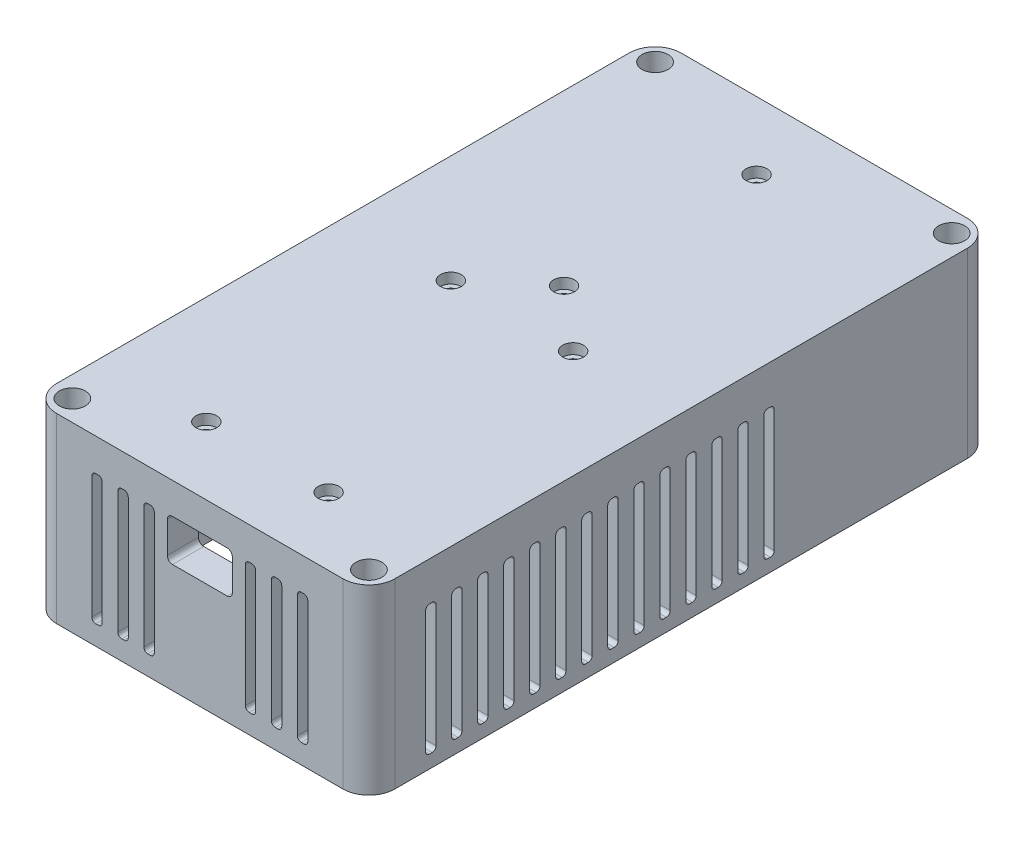
SolidWorks part; units mm, degrees
ref_plane "Front Plane" through (0, 0, 0) normal (0, 0, 1) x (1, 0, 0)
ref_plane "Top Plane" through (0, 0, 0) normal (0, 1, 0) x (1, 0, 0)
ref_plane "Right Plane" through (0, 0, 0) normal (1, 0, 0) x (0, 0, -1)
sketch "Sketch1" plane through (0, 0, 0) normal (0, 1, 0) x (1, 0, 0)
  line L0 (-26.5, 51.5) -> (-26.5, -51.5)
  line L1 (-27.5, 60) -> (27.5, 60)
  line L2 (-32.5, 55) -> (-32.5, -55)
  line L3 (-27.5, -60) -> (27.5, -60)
  line L4 (32.5, 55) -> (32.5, -55)
  line L5 (-32.5, 60) -> (32.5, -60) construction
  line L6 (-32.5, -60) -> (32.5, 60) construction
  line L7 (-24, -54) -> (24, -54)
  line L8 (26.5, 51.5) -> (26.5, -51.5)
  line L9 (-24, 54) -> (24, 54)
  line L10 (-26.5, -54) -> (26.5, -54) construction
  line L11 (-26.5, 54) -> (-26.5, -54) construction
  line L12 (26.5, 54) -> (26.5, -54) construction
  line L13 (-26.5, 54) -> (26.5, 54) construction
  arc A0 (-32.5, -55) -> (-27.5, -60) centre (-27.5, -55) ccw
  arc A1 (27.5, -60) -> (32.5, -55) centre (27.5, -55) ccw
  arc A2 (32.5, 55) -> (27.5, 60) centre (27.5, 55) ccw
  arc A3 (-27.5, 60) -> (-32.5, 55) centre (-27.5, 55) ccw
  arc A8 (-24, -54) -> (-26.5, -51.5) centre (-24, -51.5) cw
  arc A9 (-26.5, -54) -> (-26.5, -54) centre (-26.5, -54) ccw construction
  arc A10 (24, -54) -> (26.5, -51.5) centre (24, -51.5) ccw
  arc A11 (26.5, -54) -> (26.5, -54) centre (26.5, -54) ccw construction
  arc A12 (26.5, 51.5) -> (24, 54) centre (24, 51.5) ccw
  arc A13 (26.5, 54) -> (26.5, 54) centre (26.5, 54) ccw construction
  arc A14 (-24, 54) -> (-26.5, 51.5) centre (-24, 51.5) ccw
  arc A15 (-26.5, 54) -> (-26.5, 54) centre (-26.5, 54) ccw construction
  point P0 (0, 0)
  dimension "D3" = 5
  dimension "D5" = 2.5
  dimension "D1" = 120
  dimension "D2" = 65
  dimension "D4" = 6
extrude "Boss-Extrude1" add sketch "Sketch1" along normal blind 30
sketch "Sketch6" plane through (0, 30, 0) normal (0, 1, 0) x (1, 0, 0)
  line L1 (-27.5, 60) -> (27.5, 60)
  line L2 (-32.5, 55) -> (-32.5, -55)
  line L3 (-27.5, -60) -> (27.5, -60)
  line L4 (32.5, 55) -> (32.5, -55)
  line L5 (-32.5, 60) -> (32.5, -60) construction
  line L6 (-32.5, -60) -> (32.5, 60) construction
  arc A0 (-32.5, -55) -> (-27.5, -60) centre (-27.5, -55) ccw
  arc A1 (27.5, -60) -> (32.5, -55) centre (27.5, -55) ccw
  arc A2 (27.5, 60) -> (32.5, 55) centre (27.5, 55) cw
  arc A3 (-27.5, 60) -> (-32.5, 55) centre (-27.5, 55) ccw
  point P0 (0, 0)
  dimension "D3" = 5
  dimension "D1" = 120
  dimension "D2" = 65
extrude "Boss-Extrude2" add sketch "Sketch6" along normal blind 5
sketch "Sketch7" plane through (0, 0, 60) normal (0, 0, 1) x (1, 0, 0)
  line L3 (-5.25, 29) -> (5.25, 29)
  line L4 (-6.25, 28) -> (-6.25, 22)
  line L5 (-5.25, 21) -> (5.25, 21)
  line L6 (6.25, 28) -> (6.25, 22)
  line L7 (-6.25, 29) -> (6.25, 21) construction
  line L8 (-6.25, 21) -> (6.25, 29) construction
  line L9 (-27.5, 0) -> (-27.5, 16.25) construction
  line L10 (-27.5, 16.25) -> (27.5, 16.25) construction
  arc A0 (5.25, 29) -> (6.25, 28) centre (5.25, 28) cw
  arc A1 (-5.25, 29) -> (-6.25, 28) centre (-5.25, 28) ccw
  arc A2 (-6.25, 22) -> (-5.25, 21) centre (-5.25, 22) ccw
  arc A3 (5.25, 21) -> (6.25, 22) centre (5.25, 22) ccw
  point P5 (0, 25)
  dimension "D4" = 1
  dimension "D1" = 8
  dimension "D2" = 12.5
extrude "Cut-Extrude1" cut sketch "Sketch7" against normal up to surface (6 mm away) up to face at (0, 15, 54)
sketch "Sketch8" plane through (0, 0, 60) normal (0, 0, 1) x (1, 0, 0)
  line L0 (-25.75, 16.25) -> (23.75, 16.25) construction
  line L5 (-6.25, 28) -> (-6.25, 22) construction
  line L6 (-10, 28.75) -> (-9.5, 28.75)
  line L7 (-10.75, 28) -> (-10.75, 4.5)
  line L8 (-10, 3.75) -> (-9.5, 3.75)
  line L9 (-8.75, 28) -> (-8.75, 4.5)
  line L10 (-10.75, 28.75) -> (-8.75, 3.75) construction
  line L11 (-10.75, 3.75) -> (-8.75, 28.75) construction
  line L12 (-15.75, 28) -> (-15.75, 4.5)
  line L13 (-15, 28.75) -> (-14.5, 28.75)
  line L14 (-13.75, 28) -> (-13.75, 4.5)
  line L15 (-15, 3.75) -> (-14.5, 3.75)
  line L16 (-20.75, 28) -> (-20.75, 4.5)
  line L17 (-20, 28.75) -> (-19.5, 28.75)
  line L18 (-18.75, 28) -> (-18.75, 4.5)
  line L19 (-20, 3.75) -> (-19.5, 3.75)
  line L24 (8.75, 28) -> (8.75, 4.5)
  line L25 (9.5, 28.75) -> (10, 28.75)
  line L26 (10.75, 28) -> (10.75, 4.5)
  line L27 (9.5, 3.75) -> (10, 3.75)
  line L28 (6.25, 22) -> (6.25, 28) construction
  line L29 (13.75, 28) -> (13.75, 4.5)
  line L30 (14.5, 3.75) -> (15, 3.75)
  line L31 (15.75, 28) -> (15.75, 4.5)
  line L32 (14.5, 28.75) -> (15, 28.75)
  line L33 (18.75, 28) -> (18.75, 4.5)
  line L34 (19.5, 3.75) -> (20, 3.75)
  line L35 (20.75, 28) -> (20.75, 4.5)
  line L36 (19.5, 28.75) -> (20, 28.75)
  line L41 (-23.75, 28) -> (-23.75, 4.5) [skipped]
  line L42 (-25, 28.75) -> (-24.5, 28.75) [skipped]
  line L43 (-25.75, 16.25) -> (-25.75, 4.5) [skipped]
  line L44 (-25, 3.75) -> (-24.5, 3.75) [skipped]
  line L45 (24.5, 3.75) -> (25, 3.75) [skipped]
  line L47 (25.75, 28) -> (25.75, 16.25) [skipped]
  line L48 (23.75, 28) -> (23.75, 16.25) [skipped]
  line L49 (24.5, 28.75) -> (25, 28.75) [skipped]
  arc A0 (-10.75, 4.5) -> (-10, 3.75) centre (-10, 4.5) ccw
  arc A1 (-9.5, 3.75) -> (-8.75, 4.5) centre (-9.5, 4.5) ccw
  arc A2 (-9.5, 28.75) -> (-8.75, 28) centre (-9.5, 28) cw
  arc A3 (-10, 28.75) -> (-10.75, 28) centre (-10, 28) ccw
  arc A4 (-15, 28.75) -> (-15.75, 28) centre (-15, 28) ccw
  arc A5 (-15.75, 4.5) -> (-15, 3.75) centre (-15, 4.5) ccw
  arc A6 (-14.5, 28.75) -> (-13.75, 28) centre (-14.5, 28) cw
  arc A7 (-14.5, 3.75) -> (-13.75, 4.5) centre (-14.5, 4.5) ccw
  arc A8 (-20, 28.75) -> (-20.75, 28) centre (-20, 28) ccw
  arc A9 (-20.75, 4.5) -> (-20, 3.75) centre (-20, 4.5) ccw
  arc A10 (-19.5, 28.75) -> (-18.75, 28) centre (-19.5, 28) cw
  arc A11 (-19.5, 3.75) -> (-18.75, 4.5) centre (-19.5, 4.5) ccw
  arc A16 (9.5, 28.75) -> (8.75, 28) centre (9.5, 28) ccw
  arc A17 (8.75, 4.5) -> (9.5, 3.75) centre (9.5, 4.5) ccw
  arc A18 (10, 28.75) -> (10.75, 28) centre (10, 28) cw
  arc A19 (10, 3.75) -> (10.75, 4.5) centre (10, 4.5) ccw
  arc A20 (13.75, 4.5) -> (14.5, 3.75) centre (14.5, 4.5) ccw
  arc A21 (15, 3.75) -> (15.75, 4.5) centre (15, 4.5) ccw
  arc A22 (15, 28.75) -> (15.75, 28) centre (15, 28) cw
  arc A23 (14.5, 28.75) -> (13.75, 28) centre (14.5, 28) ccw
  arc A24 (18.75, 4.5) -> (19.5, 3.75) centre (19.5, 4.5) ccw
  arc A25 (20, 3.75) -> (20.75, 4.5) centre (20, 4.5) ccw
  arc A26 (20, 28.75) -> (20.75, 28) centre (20, 28) cw
  arc A27 (19.5, 28.75) -> (18.75, 28) centre (19.5, 28) ccw
  arc A32 (-25, 28.75) -> (-25.75, 28) centre (-25, 28) ccw [skipped]
  arc A33 (-24.5, 28.75) -> (-23.75, 28) centre (-24.5, 28) cw [skipped]
  arc A34 (-24.5, 3.75) -> (-23.75, 4.5) centre (-24.5, 4.5) ccw [skipped]
  arc A35 (-25.75, 4.5) -> (-25, 3.75) centre (-25, 4.5) ccw [skipped]
  arc A36 (23.75, 4.5) -> (24.5, 3.75) centre (24.5, 4.5) ccw [skipped]
  arc A37 (25, 3.75) -> (25.75, 4.5) centre (25, 4.5) ccw [skipped]
  arc A38 (25, 28.75) -> (25.75, 28) centre (25, 28) cw [skipped]
  arc A39 (24.5, 28.75) -> (23.75, 28) centre (24.5, 28) ccw [skipped]
  point P8 (-9.75, 16.25)
  dimension "D3" = 0.75
  dimension "D1" = 25
  dimension "D2" = 2
  dimension "D4" = 2.5
  dimension "D7" = 2.5
  dimension "D5" = 4
  dimension "D6" = 2
  dimension "D8" = 4
extrude "Cut-Extrude2" cut sketch "Sketch8" against normal up to surface (120 mm away) up to face at (0, 17.5, -60)
sketch "Sketch9" plane through (0, 0, 0) normal (0, -1, 0) x (1, 0, 0)
  line L0 (0, 60) -> (0, -60) construction
  line L1 (-27.5, 60) -> (27.5, 60) construction
  line L2 (27.5, -60) -> (-27.5, -60) construction
  line L3 (-32.5, 0) -> (32.5, 0) construction
  line L4 (-32.5, -55) -> (-32.5, 55) construction
  line L5 (32.5, 55) -> (32.5, -55) construction
  circle A0 centre (-28.5, 56) radius 1.05
  circle A1 centre (28.5, 56) radius 1.05
  circle A2 centre (28.5, -56) radius 1.05
  circle A3 centre (-28.5, -56) radius 1.05
  dimension "D9" = 2.1
  dimension "D10" = 2.1
  dimension "D11" = 2.1
  dimension "D12" = 2.1
  dimension "D1" = 4
  dimension "D2" = 4
  dimension "D3" = 4
  dimension "D4" = 4
  dimension "D5" = 4
  dimension "D6" = 4
  dimension "D7" = 4
  dimension "D8" = 4
extrude "Cut-Extrude4" cut sketch "Sketch9" against normal up to surface (35 mm away) up to face at (0, 35, 0)
sketch "Sketch12" plane through (0, 35, 0) normal (0, 1, 0) x (1, 0, 0)
  circle A0 centre (-28.5, 56) radius 2.5
  circle A1 centre (28.5, 56) radius 2.5
  circle A2 centre (-28.5, -56) radius 2.5
  circle A3 centre (28.5, -56) radius 2.5
extrude "Cut-Extrude5" cut sketch "Sketch12" against normal blind 30
sketch "Sketch13" plane through (-32.5, 0, 0) normal (-1, 0, 0) x (0, 0, 1)
  line L0 (0, 35) -> (0, 0) construction
  line L1 (-55, 35) -> (55, 35) construction
  line L2 (-55, 17.5) -> (55, 17.5) construction
  line L3 (-55, 35) -> (-55, 0) construction
  line L4 (55, 35) -> (55, 0) construction
  circle A0 centre (-36.7234, 17.5) radius 5.25
  dimension "D1" = 10.5
extrude "Cut-Extrude6" cut sketch "Sketch13" against normal up to surface (6 mm away) up to face at (-26.5, 15, 0)
sketch "Sketch14" plane through (-32.5, 0, 0) normal (-1, 0, 0) x (0, 0, 1)
  circle A0 centre (-36.7234, 17.5) radius 7
extrude "Cut-Extrude7" cut sketch "Sketch14" against normal blind 3
sketch "Sketch15" plane through (-32.5, 0, 0) normal (-1, 0, 0) x (0, 0, 1)
  line L0 (55, 35) -> (55, 30) construction
  line L1 (55, 35) -> (55, 0) construction
  line L2 (55, 30) -> (55, 0) construction
  line L3 (55, 15) -> (-55, 15) construction
  line L4 (-55, 35) -> (-55, 0) construction
  line L6 (-17.1494, 27.5) -> (-16.6494, 27.5)
  line L7 (-17.8994, 26.75) -> (-17.8994, 3.25)
  line L8 (-17.1494, 2.5) -> (-16.6494, 2.5)
  line L9 (-15.8994, 26.75) -> (-15.8994, 3.25)
  line L10 (-17.8994, 27.5) -> (-15.8994, 2.5) construction
  line L11 (-17.8994, 2.5) -> (-15.8994, 27.5) construction
  line L15 (-12.8994, 26.75) -> (-12.8994, 3.25)
  line L16 (-12.1494, 27.5) -> (-11.6494, 27.5)
  line L17 (-10.8994, 26.75) -> (-10.8994, 3.25)
  line L18 (-12.1494, 2.5) -> (-11.6494, 2.5)
  line L19 (-7.8994, 26.75) -> (-7.8994, 3.25)
  line L20 (-7.1494, 27.5) -> (-6.6494, 27.5)
  line L21 (-5.8994, 26.75) -> (-5.8994, 3.25)
  line L22 (-7.1494, 2.5) -> (-6.6494, 2.5)
  line L23 (-2.8994, 26.75) -> (-2.8994, 3.25)
  line L24 (-2.1494, 27.5) -> (-1.6494, 27.5)
  line L25 (-0.8994, 26.75) -> (-0.8994, 3.25)
  line L26 (-2.1494, 2.5) -> (-1.6494, 2.5)
  line L27 (2.1006, 26.75) -> (2.1006, 3.25)
  line L28 (2.8506, 27.5) -> (3.3506, 27.5)
  line L29 (4.1006, 26.75) -> (4.1006, 3.25)
  line L30 (2.8506, 2.5) -> (3.3506, 2.5)
  line L31 (7.1006, 26.75) -> (7.1006, 3.25)
  line L32 (7.8506, 27.5) -> (8.3506, 27.5)
  line L33 (9.1006, 26.75) -> (9.1006, 3.25)
  line L34 (7.8506, 2.5) -> (8.3506, 2.5)
  line L35 (12.1006, 26.75) -> (12.1006, 3.25)
  line L36 (12.8506, 27.5) -> (13.3506, 27.5)
  line L37 (14.1006, 26.75) -> (14.1006, 3.25)
  line L38 (12.8506, 2.5) -> (13.3506, 2.5)
  line L39 (17.1006, 26.75) -> (17.1006, 3.25)
  line L40 (17.8506, 27.5) -> (18.3506, 27.5)
  line L41 (19.1006, 26.75) -> (19.1006, 3.25)
  line L42 (17.8506, 2.5) -> (18.3506, 2.5)
  line L43 (22.1006, 26.75) -> (22.1006, 3.25)
  line L44 (22.8506, 27.5) -> (23.3506, 27.5)
  line L45 (24.1006, 26.75) -> (24.1006, 3.25)
  line L46 (22.8506, 2.5) -> (23.3506, 2.5)
  line L47 (27.1006, 26.75) -> (27.1006, 3.25)
  line L48 (27.8506, 27.5) -> (28.3506, 27.5)
  line L49 (29.1006, 26.75) -> (29.1006, 3.25)
  line L50 (27.8506, 2.5) -> (28.3506, 2.5)
  line L51 (32.1006, 26.75) -> (32.1006, 3.25)
  line L52 (32.8506, 27.5) -> (33.3506, 27.5)
  line L53 (34.1006, 26.75) -> (34.1006, 3.25)
  line L54 (32.8506, 2.5) -> (33.3506, 2.5)
  line L55 (37.1006, 26.75) -> (37.1006, 3.25)
  line L56 (37.8506, 27.5) -> (38.3506, 27.5)
  line L57 (39.1006, 26.75) -> (39.1006, 3.25)
  line L58 (37.8506, 2.5) -> (38.3506, 2.5)
  line L59 (42.1006, 26.75) -> (42.1006, 3.25)
  line L60 (42.8506, 27.5) -> (43.3506, 27.5)
  line L61 (44.1006, 26.75) -> (44.1006, 3.25)
  line L62 (42.8506, 2.5) -> (43.3506, 2.5)
  line L63 (47.1006, 26.75) -> (47.1006, 3.25)
  line L64 (47.8506, 27.5) -> (48.3506, 27.5)
  line L65 (49.1006, 26.75) -> (49.1006, 3.25)
  line L66 (47.8506, 2.5) -> (48.3506, 2.5)
  arc A0 (-17.8994, 3.25) -> (-17.1494, 2.5) centre (-17.1494, 3.25) ccw
  arc A1 (-16.6494, 2.5) -> (-15.8994, 3.25) centre (-16.6494, 3.25) ccw
  arc A2 (-16.6494, 27.5) -> (-15.8994, 26.75) centre (-16.6494, 26.75) cw
  arc A3 (-17.1494, 27.5) -> (-17.8994, 26.75) centre (-17.1494, 26.75) ccw
  arc A4 (-12.1494, 27.5) -> (-12.8994, 26.75) centre (-12.1494, 26.75) ccw
  arc A5 (-12.8994, 3.25) -> (-12.1494, 2.5) centre (-12.1494, 3.25) ccw
  arc A6 (-11.6494, 27.5) -> (-10.8994, 26.75) centre (-11.6494, 26.75) cw
  arc A7 (-11.6494, 2.5) -> (-10.8994, 3.25) centre (-11.6494, 3.25) ccw
  arc A8 (-7.1494, 27.5) -> (-7.8994, 26.75) centre (-7.1494, 26.75) ccw
  arc A9 (-7.8994, 3.25) -> (-7.1494, 2.5) centre (-7.1494, 3.25) ccw
  arc A10 (-6.6494, 27.5) -> (-5.8994, 26.75) centre (-6.6494, 26.75) cw
  arc A11 (-6.6494, 2.5) -> (-5.8994, 3.25) centre (-6.6494, 3.25) ccw
  arc A12 (-2.1494, 27.5) -> (-2.8994, 26.75) centre (-2.1494, 26.75) ccw
  arc A13 (-2.8994, 3.25) -> (-2.1494, 2.5) centre (-2.1494, 3.25) ccw
  arc A14 (-1.6494, 27.5) -> (-0.8994, 26.75) centre (-1.6494, 26.75) cw
  arc A15 (-1.6494, 2.5) -> (-0.8994, 3.25) centre (-1.6494, 3.25) ccw
  arc A16 (2.8506, 27.5) -> (2.1006, 26.75) centre (2.8506, 26.75) ccw
  arc A17 (2.1006, 3.25) -> (2.8506, 2.5) centre (2.8506, 3.25) ccw
  arc A18 (3.3506, 27.5) -> (4.1006, 26.75) centre (3.3506, 26.75) cw
  arc A19 (3.3506, 2.5) -> (4.1006, 3.25) centre (3.3506, 3.25) ccw
  arc A20 (7.8506, 27.5) -> (7.1006, 26.75) centre (7.8506, 26.75) ccw
  arc A21 (7.1006, 3.25) -> (7.8506, 2.5) centre (7.8506, 3.25) ccw
  arc A22 (8.3506, 27.5) -> (9.1006, 26.75) centre (8.3506, 26.75) cw
  arc A23 (8.3506, 2.5) -> (9.1006, 3.25) centre (8.3506, 3.25) ccw
  arc A24 (12.8506, 27.5) -> (12.1006, 26.75) centre (12.8506, 26.75) ccw
  arc A25 (12.1006, 3.25) -> (12.8506, 2.5) centre (12.8506, 3.25) ccw
  arc A26 (13.3506, 27.5) -> (14.1006, 26.75) centre (13.3506, 26.75) cw
  arc A27 (13.3506, 2.5) -> (14.1006, 3.25) centre (13.3506, 3.25) ccw
  arc A28 (17.8506, 27.5) -> (17.1006, 26.75) centre (17.8506, 26.75) ccw
  arc A29 (17.1006, 3.25) -> (17.8506, 2.5) centre (17.8506, 3.25) ccw
  arc A30 (18.3506, 27.5) -> (19.1006, 26.75) centre (18.3506, 26.75) cw
  arc A31 (18.3506, 2.5) -> (19.1006, 3.25) centre (18.3506, 3.25) ccw
  arc A32 (22.8506, 27.5) -> (22.1006, 26.75) centre (22.8506, 26.75) ccw
  arc A33 (22.1006, 3.25) -> (22.8506, 2.5) centre (22.8506, 3.25) ccw
  arc A34 (23.3506, 27.5) -> (24.1006, 26.75) centre (23.3506, 26.75) cw
  arc A35 (23.3506, 2.5) -> (24.1006, 3.25) centre (23.3506, 3.25) ccw
  arc A36 (27.8506, 27.5) -> (27.1006, 26.75) centre (27.8506, 26.75) ccw
  arc A37 (27.1006, 3.25) -> (27.8506, 2.5) centre (27.8506, 3.25) ccw
  arc A38 (28.3506, 27.5) -> (29.1006, 26.75) centre (28.3506, 26.75) cw
  arc A39 (28.3506, 2.5) -> (29.1006, 3.25) centre (28.3506, 3.25) ccw
  arc A40 (32.8506, 27.5) -> (32.1006, 26.75) centre (32.8506, 26.75) ccw
  arc A41 (32.1006, 3.25) -> (32.8506, 2.5) centre (32.8506, 3.25) ccw
  arc A42 (33.3506, 27.5) -> (34.1006, 26.75) centre (33.3506, 26.75) cw
  arc A43 (33.3506, 2.5) -> (34.1006, 3.25) centre (33.3506, 3.25) ccw
  arc A44 (37.8506, 27.5) -> (37.1006, 26.75) centre (37.8506, 26.75) ccw
  arc A45 (37.1006, 3.25) -> (37.8506, 2.5) centre (37.8506, 3.25) ccw
  arc A46 (38.3506, 27.5) -> (39.1006, 26.75) centre (38.3506, 26.75) cw
  arc A47 (38.3506, 2.5) -> (39.1006, 3.25) centre (38.3506, 3.25) ccw
  arc A48 (42.8506, 27.5) -> (42.1006, 26.75) centre (42.8506, 26.75) ccw
  arc A49 (42.1006, 3.25) -> (42.8506, 2.5) centre (42.8506, 3.25) ccw
  arc A50 (43.3506, 27.5) -> (44.1006, 26.75) centre (43.3506, 26.75) cw
  arc A51 (43.3506, 2.5) -> (44.1006, 3.25) centre (43.3506, 3.25) ccw
  arc A52 (47.8506, 27.5) -> (47.1006, 26.75) centre (47.8506, 26.75) ccw
  arc A53 (47.1006, 3.25) -> (47.8506, 2.5) centre (47.8506, 3.25) ccw
  arc A54 (48.3506, 27.5) -> (49.1006, 26.75) centre (48.3506, 26.75) cw
  arc A55 (48.3506, 2.5) -> (49.1006, 3.25) centre (48.3506, 3.25) ccw
  point P11 (-16.8994, 15)
  dimension "D4" = 0.75
  dimension "D1" = 5
  dimension "D2" = 25
  dimension "D3" = 2
  dimension "D5" = 14
extrude "Cut-Extrude8" cut sketch "Sketch15" against normal up to surface (65 mm away) up to face at (32.5, 17.5, 0)
sketch "Sketch18" plane through (0, 30, 0) normal (0, -1, 0) x (1, 0, 0)
  line L0 (0, 54) -> (0, 0) construction
  line L1 (-24, 54) -> (24, 54) construction
  line L2 (-26.5, 27) -> (26.5, 27)
  line L3 (26.5, 51.5) -> (26.5, -51.5) construction
  line L4 (-24, 54) -> (24, 54) construction
  circle A0 centre (-11.75, 47) radius 1.05
  circle A1 centre (11.75, 47) radius 1.05
  circle A2 centre (-11.75, 0) radius 1.05
  circle A3 centre (11.75, 0) radius 1.05
  point P10 (0, 27)
  point P20 (0, 0)
  dimension "D9" = 2.1
  dimension "D10" = 2.1
  dimension "D11" = 2.1
  dimension "D12" = 2.1
  dimension "D1" = 47
  dimension "D2" = 7
  dimension "D3" = 23.5
  dimension "D4" = 47
  dimension "D5" = 7
  dimension "D6" = 23.5
  dimension "D7" = 11.75
  dimension "D8" = 11.75
extrude "Cut-Extrude9" cut sketch "Sketch18" along direction (0, 1, 0) on the side against the normal up to next (5 mm away) contours A2 | A3 | A1 | A0
sketch "Sketch20" plane through (0, 30, 0) normal (0, -1, 0) x (1, 0, 0)
  line L0 (0, 0) -> (0, -54) construction
  line L1 (24, -54) -> (-24, -54) construction
  line L2 (26.5, -27) -> (-26.5, -27) construction
  line L3 (26.5, 51.5) -> (26.5, -51.5) construction
  line L4 (-26.5, -51.5) -> (-26.5, 51.5) construction
  line L5 (27.5, -60) -> (-27.5, -60) construction
  circle A0 centre (0, -10) radius 1.05
  circle A1 centre (0, -47) radius 1.05
  circle A2 centre (11.75, 0) radius 1.05 construction
  dimension "D3" = 2.1
  dimension "D4" = 2.1
  dimension "D1" = 37
  dimension "D2" = 10
  dimension "D5" = 13
extrude "Cut-Extrude11" cut sketch "Sketch20" against normal up to surface (5 mm away) up to face at (-11.75, 35, 48.05)
sketch "Sketch19" plane through (0, 35, 0) normal (0, 1, 0) x (1, 0, 0)
  circle A0 centre (-11.75, 0) radius 2
  circle A1 centre (11.75, 0) radius 2
  circle A2 centre (11.75, -47) radius 2
  circle A3 centre (-11.75, -47) radius 2
  circle A4 centre (0, 10) radius 2
  circle A5 centre (0, 47) radius 2
  dimension "D1" = 4
  dimension "D2" = 4
  dimension "D3" = 4
  dimension "D4" = 4
  dimension "D5" = 4
  dimension "D6" = 4
extrude "Cut-Extrude10" cut sketch "Sketch19" against normal blind 2
